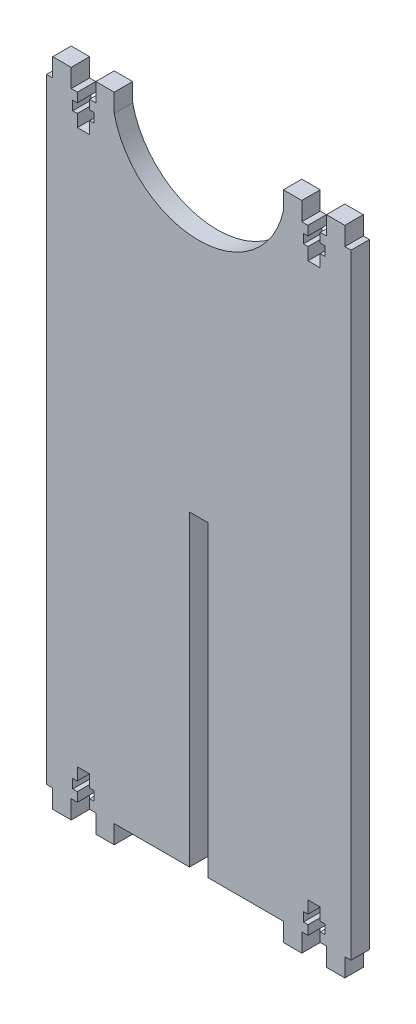
SolidWorks part; units mm, degrees
ref_plane "Front Plane" through (0, 0, 0) normal (0, 0, 1) x (1, 0, 0)
ref_plane "Top Plane" through (0, 0, 0) normal (0, 1, 0) x (1, 0, 0)
ref_plane "Right Plane" through (0, 0, 0) normal (1, 0, 0) x (0, 0, -1)
sketch "Esquisse1" plane through (0, 0, 0) normal (0, 0, 1) x (1, 0, 0)
  line L0 (-40.6367, 39.0536) -> (-42.6367, 39.0536)
  line L1 (-42.6367, 39.0536) -> (-42.6367, -160.9464)
  line L2 (-42.6367, -160.9464) -> (-40.6367, -160.9464)
  line L3 (-20.6367, -160.9464) -> (3.8633, -160.9464)
  line L4 (3.8633, -160.9464) -> (3.8633, -60.9464)
  line L5 (3.8633, -60.9464) -> (9.8633, -60.9464)
  line L6 (9.8633, -60.9464) -> (9.8633, -160.9464)
  line L7 (9.8633, -160.9464) -> (34.3633, -160.9464)
  line L8 (54.3633, -160.9464) -> (56.3633, -160.9464)
  line L9 (56.3633, -160.9464) -> (56.3633, 39.0536)
  line L10 (56.3633, 39.0536) -> (54.3633, 39.0536)
  line L11 (34.3633, 39.0536) -> (-20.6367, 39.0536)
  line L12 (6.8633, 130.4243) -> (6.8633, -128.0179) construction
  point P18 (6.8633, -60.9464)
  point P19 (6.8633, 39.0536)
  line B0 (-27.1367, 36.0536) -> (-27.1367, 33.0536)
  line B1 (-32.6367, 33.0536) -> (-32.6367, 29.0536)
  line B2 (-28.6367, 29.0536) -> (-28.6367, 33.0536)
  line B3 (-27.1367, 33.0536) -> (-28.6367, 33.0536)
  line B4 (-30.6367, 39.0536) -> (-30.6367, 28.8329) construction
  line B5 (-28.6367, 39.0536) -> (-26.6367, 39.0536)
  line B6 (-26.6367, 45.0536) -> (-20.6367, 45.0536)
  line B7 (-20.6367, 45.0536) -> (-20.6367, 39.0536)
  line B8 (-26.6367, 45.0536) -> (-26.6367, 39.0536)
  line B9 (-32.6367, 39.0536) -> (-34.6367, 39.0536)
  line B10 (-34.6367, 39.0536) -> (-34.6367, 45.0536)
  line B11 (-34.6367, 45.0536) -> (-40.6367, 45.0536)
  line B12 (-40.6367, 45.0536) -> (-40.6367, 39.0536)
  line B13 (-28.6367, 39.0536) -> (-32.6367, 39.0536) construction
  line B14 (-32.6367, 39.0536) -> (-32.6367, 36.0536)
  line B15 (-32.6367, 33.0536) -> (-34.1367, 33.0536)
  line B16 (-34.1367, 36.0536) -> (-32.6367, 36.0536)
  line B17 (-32.6367, 29.0536) -> (-28.6367, 29.0536)
  line B18 (-28.6367, 36.0536) -> (-27.1367, 36.0536)
  line B19 (-34.1367, 33.0536) -> (-34.1367, 36.0536)
  line B20 (-28.6367, 36.0536) -> (-28.6367, 39.0536)
  line B21 (-30.6367, 29.0536) -> (-30.6367, 39.0536) construction
  line B22 (47.8633, 36.0536) -> (47.8633, 33.0536)
  line B23 (42.3633, 33.0536) -> (42.3633, 29.0536)
  line B24 (46.3633, 29.0536) -> (46.3633, 33.0536)
  line B25 (47.8633, 33.0536) -> (46.3633, 33.0536)
  line B26 (44.3633, 39.0536) -> (44.3633, 28.8329) construction
  line B27 (46.3633, 39.0536) -> (48.3633, 39.0536)
  line B28 (48.3633, 45.0536) -> (54.3633, 45.0536)
  line B29 (54.3633, 45.0536) -> (54.3633, 39.0536)
  line B30 (48.3633, 45.0536) -> (48.3633, 39.0536)
  line B31 (42.3633, 39.0536) -> (40.3633, 39.0536)
  line B32 (40.3633, 39.0536) -> (40.3633, 45.0536)
  line B33 (40.3633, 45.0536) -> (34.3633, 45.0536)
  line B34 (34.3633, 45.0536) -> (34.3633, 39.0536)
  line B35 (46.3633, 39.0536) -> (42.3633, 39.0536) construction
  line B36 (42.3633, 39.0536) -> (42.3633, 36.0536)
  line B37 (42.3633, 33.0536) -> (40.8633, 33.0536)
  line B38 (40.8633, 36.0536) -> (42.3633, 36.0536)
  line B39 (42.3633, 29.0536) -> (46.3633, 29.0536)
  line B40 (46.3633, 36.0536) -> (47.8633, 36.0536)
  line B41 (40.8633, 33.0536) -> (40.8633, 36.0536)
  line B42 (46.3633, 36.0536) -> (46.3633, 39.0536)
  line B43 (44.3633, 29.0536) -> (44.3633, 39.0536) construction
  line B44 (-34.1367, -157.9464) -> (-34.1367, -154.9464)
  line B45 (-28.6367, -154.9464) -> (-28.6367, -150.9464)
  line B46 (-32.6367, -150.9464) -> (-32.6367, -154.9464)
  line B47 (-34.1367, -154.9464) -> (-32.6367, -154.9464)
  line B48 (-30.6367, -160.9464) -> (-30.6367, -150.7256) construction
  line B49 (-32.6367, -160.9464) -> (-34.6367, -160.9464)
  line B50 (-34.6367, -166.9464) -> (-40.6367, -166.9464)
  line B51 (-40.6367, -166.9464) -> (-40.6367, -160.9464)
  line B52 (-34.6367, -166.9464) -> (-34.6367, -160.9464)
  line B53 (-28.6367, -160.9464) -> (-26.6367, -160.9464)
  line B54 (-26.6367, -160.9464) -> (-26.6367, -166.9464)
  line B55 (-26.6367, -166.9464) -> (-20.6367, -166.9464)
  line B56 (-20.6367, -166.9464) -> (-20.6367, -160.9464)
  line B57 (-32.6367, -160.9464) -> (-28.6367, -160.9464) construction
  line B58 (-28.6367, -160.9464) -> (-28.6367, -157.9464)
  line B59 (-28.6367, -154.9464) -> (-27.1367, -154.9464)
  line B60 (-27.1367, -157.9464) -> (-28.6367, -157.9464)
  line B61 (-28.6367, -150.9464) -> (-32.6367, -150.9464)
  line B62 (-32.6367, -157.9464) -> (-34.1367, -157.9464)
  line B63 (-27.1367, -154.9464) -> (-27.1367, -157.9464)
  line B64 (-32.6367, -157.9464) -> (-32.6367, -160.9464)
  line B65 (-30.6367, -150.9464) -> (-30.6367, -160.9464) construction
  line B66 (40.8633, -157.9464) -> (40.8633, -154.9464)
  line B67 (46.3633, -154.9464) -> (46.3633, -150.9464)
  line B68 (42.3633, -150.9464) -> (42.3633, -154.9464)
  line B69 (40.8633, -154.9464) -> (42.3633, -154.9464)
  line B70 (44.3633, -160.9464) -> (44.3633, -150.7256) construction
  line B71 (42.3633, -160.9464) -> (40.3633, -160.9464)
  line B72 (40.3633, -166.9464) -> (34.3633, -166.9464)
  line B73 (34.3633, -166.9464) -> (34.3633, -160.9464)
  line B74 (40.3633, -166.9464) -> (40.3633, -160.9464)
  line B75 (46.3633, -160.9464) -> (48.3633, -160.9464)
  line B76 (48.3633, -160.9464) -> (48.3633, -166.9464)
  line B77 (48.3633, -166.9464) -> (54.3633, -166.9464)
  line B78 (54.3633, -166.9464) -> (54.3633, -160.9464)
  line B79 (42.3633, -160.9464) -> (46.3633, -160.9464) construction
  line B80 (46.3633, -160.9464) -> (46.3633, -157.9464)
  line B81 (46.3633, -154.9464) -> (47.8633, -154.9464)
  line B82 (47.8633, -157.9464) -> (46.3633, -157.9464)
  line B83 (46.3633, -150.9464) -> (42.3633, -150.9464)
  line B84 (42.3633, -157.9464) -> (40.8633, -157.9464)
  line B85 (47.8633, -154.9464) -> (47.8633, -157.9464)
  line B86 (42.3633, -157.9464) -> (42.3633, -160.9464)
  line B87 (44.3633, -150.9464) -> (44.3633, -160.9464) construction
  dimension "D1" = 200
  dimension "D2" = 75
  dimension "D3" = 6
  dimension "D5" = 100
  dimension "D6" = 99
sketch_block_instance "Plots M4 ep6 tol0.0-2"
sketch_block "Plots M4 ep6 tol0.0" parameters "D1"=10, "D2"=6, "D3"=6, "D4"=7, "D5"=4, "D6"=3, "D7"=3, "D8"=10
sketch_block_instance "Plots M4 ep6 tol0.0-3"
sketch_block_instance "Plots M4 ep6 tol0.0-4"
sketch_block_instance "Plots M4 ep6 tol0.0-7"
extrude "Boss.-Extru.1" add sketch "Esquisse1" along normal blind 6 contours L12 L11 B7 B6 B8 B5 B20 B18 B0 B3 B2 B17 B1 B15 B19 B16 B14 B9 B10 B11 B12 L0 L1 L2 B51 B50 B52 B49 B64 B62 B44 B47 B46 B61 B45 B59 B63 B60 B58 B53 B54 B55 B56 L3 L4 L5 | L11 L12 L5 L6 L7 B73 B72 B74 B71 B86 B84 B66 B69 B68 B83 B67 B81 B85 B82 B80 B75 B76 B77 B78 L8 L9 L10 B29 B28 B30 B27 B42 B40 B22 B25 B24 B39 B23 B37 B41 B38 B36 B31 B32 B33 B34
sketch "Esquisse2" plane through (0, 0, 6) normal (0, 0, 1) x (1, 0, 0)
  line L0 (-20.6367, 39.0536) -> (34.3633, 39.0536)
  line L1 (-16.6803, 17.0536) -> (39.0941, 17.0536) construction
  arc A0 (-20.6367, 39.0536) -> (34.3633, 39.0536) centre (6.8633, 45.2411) ccw
  dimension "D1" = 22
extrude "Enlèv. mat.-Extru.1" cut sketch "Esquisse2" against normal blind 10
